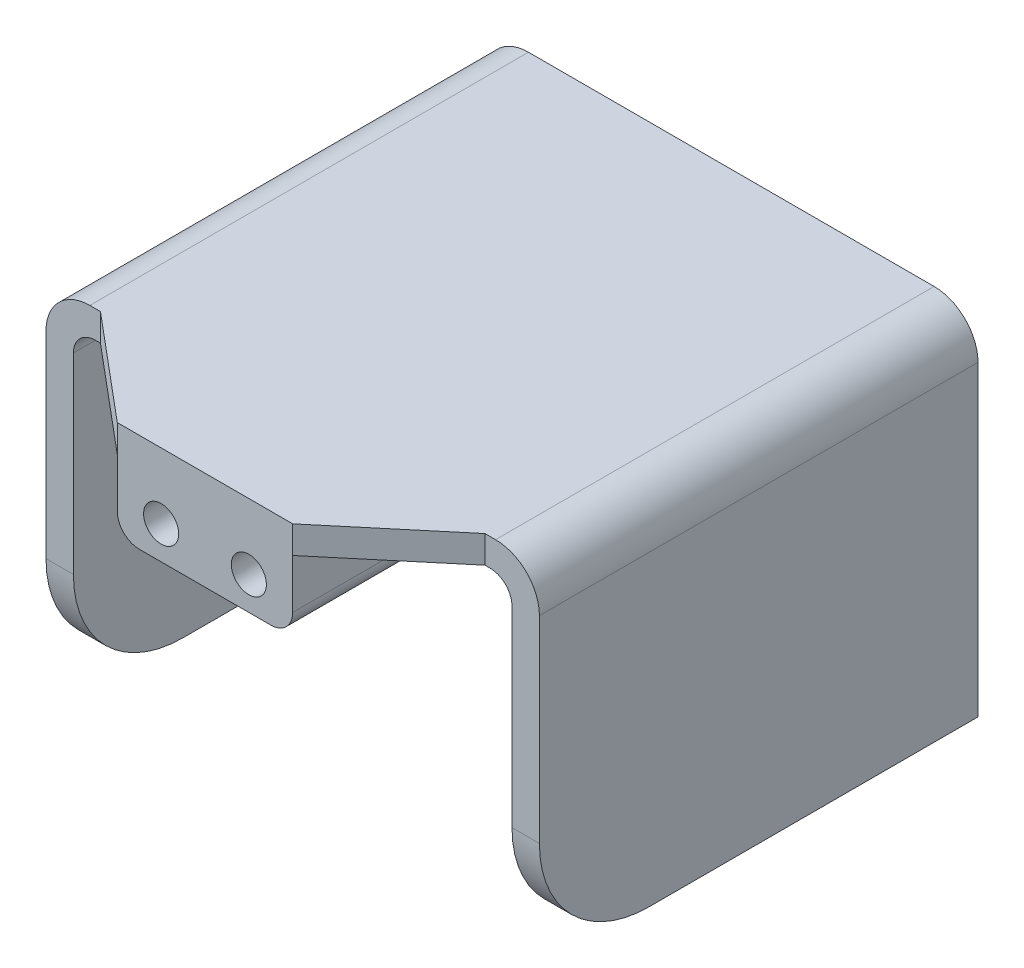
SolidWorks part; units mm, degrees
ref_plane "Front Plane" through (0, 0, 0) normal (0, 0, 1) x (1, 0, 0)
ref_plane "Top Plane" through (0, 0, 0) normal (0, 1, 0) x (1, 0, 0)
ref_plane "Right Plane" through (0, 0, 0) normal (1, 0, 0) x (0, 0, -1)
sketch "Sketch1" plane through (0, 0, 0) normal (0, 0, 1) x (1, 0, 0)
  line L0 (-50, 0) -> (0, 0) construction
  line L1 (0, 0) -> (0, 50) construction
  line L2 (-50, 0) -> (0, 0) construction
  line L5 (-45, 53.75) -> (-20, 53.75)
  line L10 (46.25, 60) -> (-46.25, 60)
  line L11 (-50, 48.75) -> (-50, -20)
  line L17 (-20, 53.75) -> (-20, 42.5)
  line L18 (-15, 37.5) -> (15, 37.5)
  line L21 (-50, -20) -> (-56.25, -20)
  line L22 (-40, 45) -> (0, 45) construction
  line L23 (-56.25, -20) -> (-56.25, 50)
  line L24 (20, 53.75) -> (20, 42.5)
  line L25 (45, 53.75) -> (20, 53.75)
  line L26 (50, 48.75) -> (50, -20)
  line L27 (50, -20) -> (56.25, -20)
  line L28 (56.25, -20) -> (56.25, 50)
  circle A1 centre (-50, 0) radius 41 construction
  circle A3 centre (-50, 0) radius 49 construction
  arc A8 (-46.25, 60) -> (-56.25, 50) centre (-46.25, 50) ccw
  arc A9 (-45, 53.75) -> (-50, 48.75) centre (-45, 48.75) ccw
  circle A10 centre (-10, 45) radius 4
  circle A11 centre (10, 45) radius 4
  arc A12 (20, 42.5) -> (15, 37.5) centre (15, 42.5) cw
  arc A15 (-20, 42.5) -> (-15, 37.5) centre (-15, 42.5) ccw
  arc A16 (45, 53.75) -> (50, 48.75) centre (45, 48.75) cw
  arc A17 (46.25, 60) -> (56.25, 50) centre (46.25, 50) cw
  point P9 (0, 0)
  point P12 (-53.125, -20)
  point P22 (0, 37.5)
  point P33 (0, 37.5)
  point P39 (0, 60)
  point P44 (-40, 37.5)
  dimension "D1" = 37.5
  dimension "D4" = 10
  dimension "D5" = 6.25
  dimension "D11" = 8
  dimension "D13" = 5
  dimension "D9" = 10
  dimension "D10" = 5
  dimension "D2" = 22.5
  dimension "D3" = 7.5
  dimension "D6" = 80
  dimension "D7" = 50
  dimension "D8" = 6.25
  dimension "D12" = 20
extrude "Boss-Extrude1" add sketch "Sketch1" along normal blind 120
sketch "Sketch2" plane through (0, 0, 0) normal (0, 1, 0) x (1, 0, 0)
  line L0 (0, 0) -> (0, -120) construction
  line L2 (-20, -120) -> (-43.8351, -100)
  line L3 (-43.8351, -100) -> (-56.25, -100)
  line L4 (-56.25, -100) -> (-56.25, -170)
  line L5 (-56.25, -170) -> (56.25, -170)
  line L6 (-20, -120) -> (20, -120)
  line L9 (56.25, -100) -> (56.25, -170)
  line L10 (43.8351, -100) -> (56.25, -100)
  line L11 (20, -120) -> (43.8351, -100)
  line L12 (46.25, -120) -> (-46.25, -120) construction
  line L13 (-56.25, -120) -> (-56.25, 0) construction
  point P19 (0, -170)
  dimension "D1" = 40
  dimension "D2" = 20
  dimension "D5" = 50
extrude "Cut-Extrude2" cut sketch "Sketch2" against normal mid plane 339
sketch "Sketch4" plane through (0, 0, 0) normal (1, 0, 0) x (0, 0, -1)
  line L0 (0, 60) -> (0, -20)
  line L1 (0, -20) -> (28, 13.2665)
  line L3 (28, 26.7335) -> (0, 60)
  line L5 (28, 26.7335) -> (28, 13.2665) construction
  line L6 (28, 20) -> (0, 20) construction
  arc A0 (28, 13.2665) -> (28, 26.7335) centre (20, 20) ccw
  circle A1 centre (20, 20) radius 5
  point P4 (0, 0)
  point P7 (8.3385, -59.1211)
  point P10 (36.3747, 0)
  point P14 (0, 0)
  point P16 (20.8723, 0)
  point P17 (7.9986, 0)
  point P18 (21.2218, 0)
  point P19 (21.1854, 5.0032)
  point P20 (13.1286, 0)
  dimension "D4" = 10
  dimension "D1" = 20
  dimension "D2" = 8
extrude "Boss-Extrude3" add sketch "Sketch4" along normal mid plane 6.25
sketch "Sketch6" plane through (0, -20, 0) normal (0, -1, 0) x (1, 0, 0)
  line L1 (-53.3439, 0) -> (53.1713, 0)
  line L3 (-53.3439, 6.25) -> (53.1713, 6.25)
  line L5 (-53.3439, 6.25) -> (-53.3439, 0)
  line L6 (53.1713, 6.25) -> (53.1713, 0)
  dimension "D1" = 6.25
extrude "Boss-Extrude5" add sketch "Sketch6" against normal up to surface (73.75 mm away) up to face at (-34.767, 53.75, 64)
fillet "Fillet1" radius 25 2 edges at (-53.125, -20, 100) (53.125, -20, 100)
